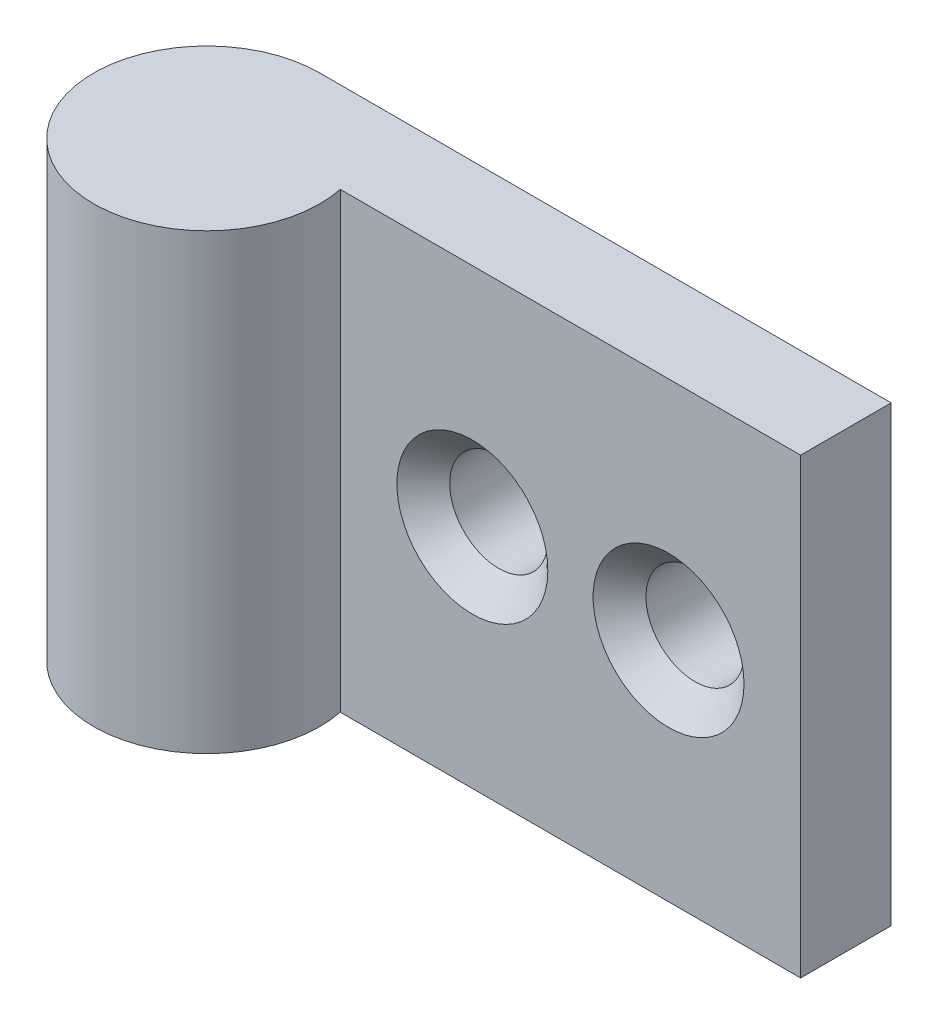
SolidWorks part; units mm, degrees
ref_plane "前视基准面" through (0, 0, 0) normal (0, 0, 1) x (1, 0, 0)
ref_plane "上视基准面" through (0, 0, 0) normal (0, 1, 0) x (1, 0, 0)
ref_plane "右视基准面" through (0, 0, 0) normal (1, 0, 0) x (0, 0, -1)
other "Configuration Table"
sketch "草图1" plane through (0, 0, 0) normal (0, 0, 1) x (1, 0, 0)
  line L0 (0, 0) -> (30.5, 0)
  line L1 (30.5, 0) -> (30.5, -30)
  line L2 (30.5, -30) -> (0, -30)
  line L3 (0, -30) -> (0, 0)
extrude "凸台-拉伸1" add sketch "草图1" along normal blind 6
sketch "草图2" plane through (0, 0, 6) normal (0, 0, 1) x (1, 0, 0)
  line L0 (30.5, -15) -> (0, -15)
  line L1 (30.5, -30) -> (30.5, 0) construction
  line L2 (0, 0) -> (0, -30) construction
  line L3 (15.25, -15) -> (8.75, -15)
  line L4 (15.25, -15) -> (21.75, -15)
  circle A0 centre (21.75, -15) radius 3.25
  circle A1 centre (8.75, -15) radius 3.25
hole_wizard "M6 内六角花形半沉头螺钉的锥形沉头孔1" positions "草图3" profile "草图4" countersink size "M6" standard "GB" end condition through all
sketch "草图3" plane through (0, 0, 6) normal (0, 0, 1) x (1, 0, 0)
  point P0 (8.75, -15)
  point P3 (21.75, -15)
sketch "草图4" plane through (8.75, -15, 6) normal (1, 0, 0) x (0, -1, 0)
  line L0 (0, 0) -> (0, 6)
  line L1 (0, 6) -> (3.25, 6)
  line L2 (3.25, 6) -> (3.25, 1.75)
  line L3 (3.25, 1.75) -> (5, 0)
  line L5 (5, 0) -> (0, 0)
  line L6 (-3.25, 1.75) -> (-5, 0) construction
  line L11 (0, -6.35) -> (0, 107.95) construction
  dimension "通孔孔直径" = 6.5
  dimension "通孔孔深度" = 6
  dimension "近端锥形沉头孔直径" = 10
  dimension "近端锥形沉头孔角度" = 90
sketch "草图5" plane through (0, -30, 0) normal (0, -1, 0) x (1, 0, 0)
  line L0 (0, 0) -> (-15, 0)
  line L1 (-7.5, 0) -> (-7.5, 6)
  line L2 (-7.5, 6) -> (0, 6)
  line L3 (0, 6) -> (0, 0) construction
  circle A1 centre (-7.3485, 7.5) radius 7.5
  dimension "D1" = 7.5
  dimension "D2" = 15
extrude "凸台-拉伸3" add sketch "草图5" against normal up to surface (30 mm away)
